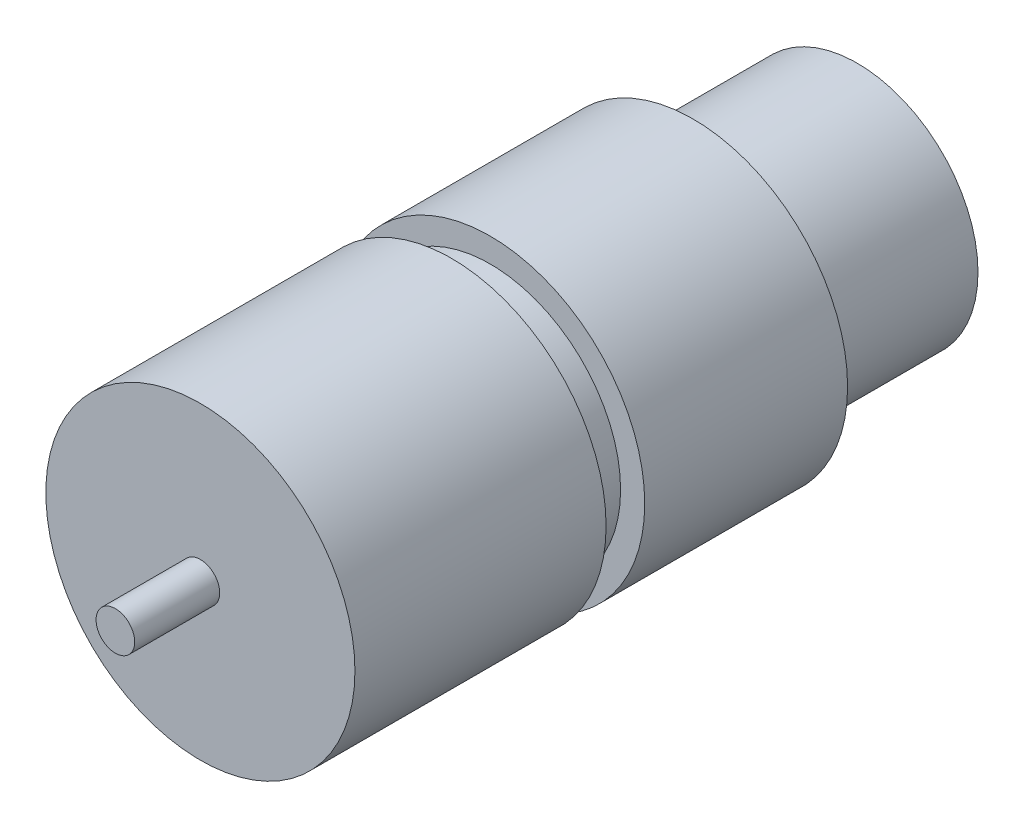
SolidWorks part; units mm, degrees
ref_plane "Спереди" through (0, 0, 0) normal (0, 0, 1) x (1, 0, 0)
ref_plane "Сверху" through (0, 0, 0) normal (0, 1, 0) x (1, 0, 0)
ref_plane "Справа" through (0, 0, 0) normal (1, 0, 0) x (0, 0, -1)
sketch "Эскиз1" plane through (0, 0, 0) normal (0, 0, 1) x (1, 0, 0)
  circle A0 centre (0, 0) radius 12.5
  dimension "D1" = 25
extrude "Вытянуть1" add sketch "Эскиз1" along normal blind 17
sketch "Эскиз2" plane through (0, 0, 17) normal (0, 0, 1) x (1, 0, 0)
  circle A0 centre (0, 0) radius 16
  dimension "D1" = 32
extrude "Вытянуть2" add sketch "Эскиз2" along normal blind 51
sketch "Эскиз3" plane through (0, 0, 68) normal (0, 0, 1) x (1, 0, 0)
  circle A0 centre (0, 0) radius 2
  dimension "D1" = 4
extrude "Вытянуть3" add sketch "Эскиз3" along normal blind 8.8
ref_plane "Плоскость1" through (0, 0, 69.8) normal (0, 0, 1) x (1, 0, 0)
ref_plane "Плоскость2" through (0, 0, 38) normal (0, 0, 1) x (1, 0, 0)
sketch "Эскиз7" plane through (0, 0, 38) normal (0, 0, 1) x (1, 0, 0)
  circle A0 centre (0, 0) radius 13.5
  circle A1 centre (0, 0) radius 20.7825
  dimension "D1" = 27
  dimension "D2" = 41.565
extrude "Вытянуть8" cut sketch "Эскиз7" along normal blind 4
